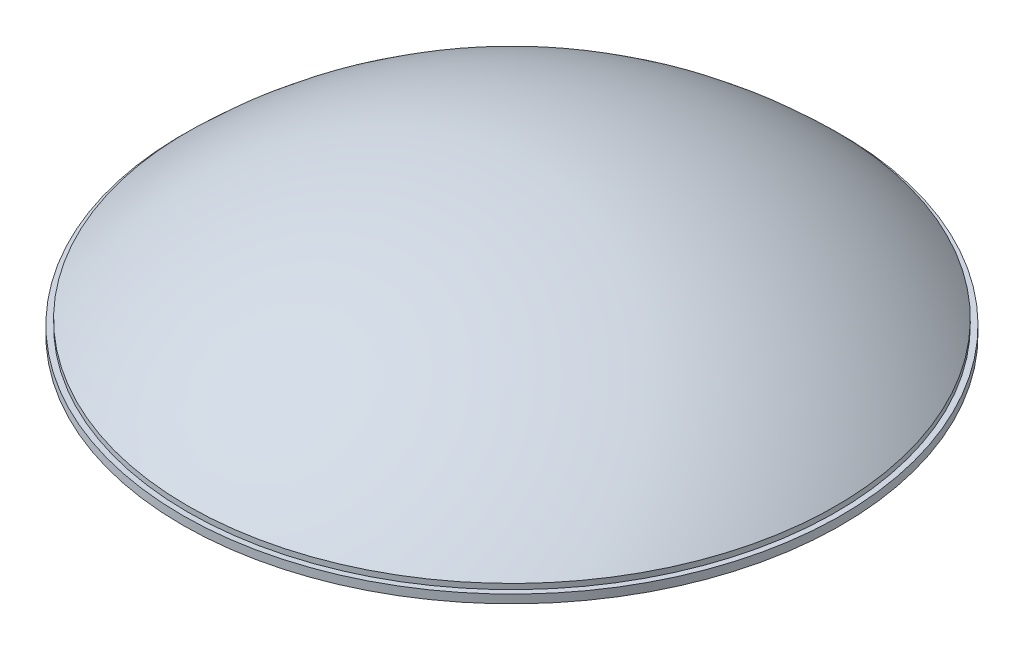
SolidWorks part; units mm, degrees
material "Acrylic (Medium-high impact)"
ref_plane "Front" through (0, 0, 0) normal (0, 0, 1) x (1, 0, 0)
ref_plane "Top" through (0, 0, 0) normal (0, 1, 0) x (1, 0, 0)
ref_plane "Right" through (0, 0, 0) normal (1, 0, 0) x (0, 0, -1)
sketch "Sketch1" plane through (0, 0, 0) normal (1, 0, 0) x (0, 0, -1)
  line L0 (0, 342) -> (0, 332) construction
  line L1 (242.6582, 241) -> (246.5, 241) construction
  line L2 (246.5, 241) -> (246.5, 229) construction
  line L3 (246.5, 229) -> (240.3809, 229) construction
  line L4 (0, 332) -> (0, 0) construction
  line L5 (0, 0) -> (53.5006, 337.7894) construction
  line L6 (26.55, 278) -> (44.0309, 278) construction
  line L7 (26.55, 258) -> (40.8632, 258) construction
  line L8 (26.25, 284) -> (26.25, 235.5) construction
  line L9 (23.25, 232.5) -> (0, 232.5) construction
  line L10 (26.55, 278) -> (26.55, 258) construction
  line L11 (22.2, 232.5) -> (22.2, 210.5) construction
  line L12 (21.2, 209.5) -> (0, 209.5) construction
  line L13 (49.2591, 319) -> (50.7013, 328.1057) construction
  line L14 (49.2591, 319) -> (39.2252, 310.1228) construction
  line L15 (29.1813, 290.9057) -> (36.1857, 297.6697) construction
  line L16 (27, 278) -> (27, 279) construction
  line L17 (27, 279) -> (42, 279) construction
  line L18 (42, 279) -> (42, 278) construction
  line L19 (26.4, 284) -> (43.7156, 284) construction
  line L20 (43.7156, 284) -> (48.9147, 316.8261) construction
  line L21 (48.4509, 317.3504) -> (40.8872, 310.6585) construction
  line L22 (40.5498, 309.9096) -> (40.5498, 304.1375) construction
  line L23 (29.2855, 290.7978) -> (36.2899, 297.5618) construction
  line L24 (36.2899, 297.5618) -> (38.7788, 299.9654) construction
  line L25 (48.4509, 317.3504) -> (48.9147, 316.8261) construction
  line L26 (30, 284) -> (30, 279) construction
  line L27 (40.7818, 311.5) -> (41.2457, 310.9757) construction
  line L28 (40, 284) -> (40, 279) construction
  line L29 (49.2591, 319) -> (49.7229, 318.4757) construction
  line L30 (49.7229, 318.4757) -> (48.4509, 317.3504) construction
  arc A0 (0, 342) -> (242.6582, 241) centre (0, 0) cw construction
  arc A1 (0, 332) -> (240.3809, 229) centre (0, 0) cw construction
  arc A2 (0, 330) -> (36.419, 314.7024) centre (0, 279) cw construction
  arc A3 (26.25, 284) -> (29.1813, 290.9057) centre (35.85, 284) cw construction
  arc A4 (23.25, 232.5) -> (26.25, 235.5) centre (23.25, 235.5) ccw construction
  arc A5 (36.1857, 297.6697) -> (36.419, 314.7024) centre (27.8498, 306.3018) ccw construction
  arc A6 (21.2, 209.5) -> (22.2, 210.5) centre (21.2, 210.5) ccw construction
  arc A7 (26.4, 284) -> (29.2855, 290.7978) centre (35.85, 284) cw construction
  arc A8 (40.5498, 309.9096) -> (40.8872, 310.6585) centre (41.5498, 309.9096) cw construction
  arc A9 (36.2899, 297.5618) -> (36.5261, 314.8074) centre (27.8498, 306.3018) ccw construction
  arc A10 (38.7788, 299.9654) -> (40.5498, 304.1375) centre (34.7498, 304.1375) ccw construction
  point P21 (0, 279)
  point P34 (22.2, 209.5)
  dimension "D1" = 342
  dimension "D2" = 332
  dimension "D16" = 51
  dimension "D17" = 9.6
  dimension "D19" = 140.5
  dimension "D20" = 12
  dimension "D21" = 51.5
  dimension "D23" = 3
  dimension "D24" = 1
  dimension "D31" = 1
  dimension "D32" = 5.8
  dimension "D3" = 241
  dimension "D4" = 229
  dimension "D5" = 246.5
  dimension "D6" = 9
  dimension "D7" = 278
  dimension "D8" = 20
  dimension "D9" = 26.25
  dimension "D10" = 0.3
  dimension "D11" = 232.5
  dimension "D12" = 23
  dimension "D13" = 22.2
  dimension "D14" = 1.25
  dimension "D15" = 97.5
  dimension "D18" = 44
  dimension "D22" = 13
  dimension "D25" = 15
  dimension "D26" = 1
  dimension "D27" = 27
  dimension "D28" = 0.7
  dimension "D29" = 0.7
  dimension "D33" = 30
  dimension "D34" = 5
  dimension "D35" = 10
  dimension "D36" = 0.7
  dimension "D37" = 7.5
  dimension "D30" = 0.15
sketch "Sketch2" plane through (0, 0, 0) normal (1, 0, 0) x (0, 0, -1)
  line L0 (246.5, 236.9583) -> (242.5, 236.9583) construction
  line L1 (242.5, 236.9583) -> (242.5, 241.1592)
  line L2 (246.5, 236.9583) -> (246.5, 230.9583) construction
  line L3 (0, 342) -> (0, 332) construction
  line L4 (244.5, 228.547) -> (-244.5, 228.547) construction
  line L5 (246.5, 237.0691) -> (246.5, 236.9583) construction
  line L6 (246.5, 241) -> (246.5, 229) construction
  line L7 (0, 342) -> (0, 332)
  line L8 (244.5, 228.547) -> (244.5, 230.96) construction
  line L9 (244.5, 229.7535) -> (240.1118, 229.7535) construction
  line L10 (242.5, 236.9583) -> (232.5398, 236.9583) construction
  line L11 (242.5, 241.1592) -> (238.5, 241.1592)
  line L12 (246.5, 230.9583) -> (238.5, 230.9583) construction
  line L13 (238.5, 241.1592) -> (238.5, 245.1158)
  line L14 (242.5, 236.9583) -> (242.5, 234.9561)
  line L15 (242.5, 234.9561) -> (234.5626, 234.9561)
  arc A1 (240.3809, 229) -> (0, 332) centre (0, 0) ccw construction
  arc A2 (246.5, 237.0691) -> (238.5, 245.1158) centre (0, 0) ccw construction
  arc A3 (238.5, 245.1158) -> (0, 342) centre (0, 0) ccw
  arc A4 (234.5626, 234.9561) -> (0, 332) centre (0, 0) ccw
  dimension "D1" = 4
  dimension "D2" = 8
  dimension "D3" = 6
  dimension "D4" = 2.4113
  dimension "D5" = 4.3882
  dimension "D6" = 4
  dimension "D7" = 2.0022
revolve "Revolve1" add sketch "Sketch2" angle 360 about L7
